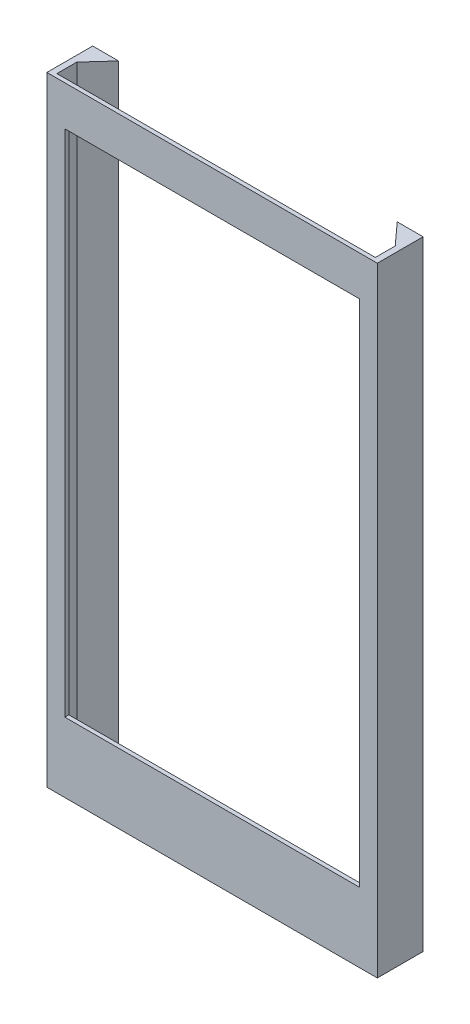
SolidWorks part; units mm, degrees
ref_plane "Alzado" through (0, 0, 0) normal (0, 0, 1) x (1, 0, 0)
ref_plane "Planta" through (0, 0, 0) normal (0, 1, 0) x (1, 0, 0)
ref_plane "Vista lateral" through (0, 0, 0) normal (1, 0, 0) x (0, 0, -1)
sketch "Croquis1" plane through (0, 0, 0) normal (0, 0, 1) x (1, 0, 0)
  line L0 (-40, 77) -> (-41.5, 77)
  line L1 (-40, -77) -> (40, -77) construction
  line L2 (-40, -77) -> (-40, 77) construction
  line L3 (-40, 77) -> (40, 77)
  line L4 (40, -77) -> (40, 77) construction
  line L5 (-40, -77) -> (40, 77) construction
  line L6 (-40, 77) -> (40, -77) construction
  line L7 (-37, 67) -> (37, 67)
  line L8 (-37, 67) -> (-37, -61)
  line L9 (-37, -61) -> (37, -61)
  line L10 (37, 67) -> (37, -61)
  line L11 (-37, 67) -> (37, -61) construction
  line L12 (-37, -61) -> (37, 67) construction
  line L13 (-41.5, 77) -> (-41.5, -78.5)
  line L14 (-41.5, -78.5) -> (41.5, -78.5)
  line L15 (41.5, -78.5) -> (41.5, 77)
  line L16 (41.5, 77) -> (40, 77)
  point P0 (0, 0)
  point P10 (0, 3)
  dimension "D1" = 80
  dimension "D2" = 154
  dimension "D3" = 10
  dimension "D4" = 3
  dimension "D5" = 3
  dimension "D6" = 16
  dimension "D7" = 1.5
  dimension "D8" = 1.5
  dimension "D9" = 1.5
extrude "Saliente-Extruir1" add sketch "Croquis1" along normal blind 11.5
sketch "Croquis2" plane through (0, 0, 0) normal (0, 0, -1) x (-1, 0, 0)
  line L1 (-40, 77) -> (40, 77)
  line L2 (-40, 77) -> (-40, -77)
  line L3 (-40, -77) -> (40, -77)
  line L4 (40, 77) -> (40, -77)
  line L5 (-40, 77) -> (40, -77) construction
  line L6 (-40, -77) -> (40, 77) construction
  point P4 (0, 0)
extrude "Cortar-Extruir1" cut sketch "Croquis2" against normal blind 10.5
sketch "Croquis3" plane through (0, -77, 0) normal (0, 1, 0) x (1, 0, 0)
  line L0 (0, 0) -> (0, 50000) construction
  line L1 (-40, -10.5) -> (-40, 0) construction
  line L3 (-40, -5.5) -> (-35, 0)
  line L4 (-35, 0) -> (-40, 0)
  line L5 (-40, 0) -> (-40, -5.5)
  line L6 (-40, -10.5) -> (40, -10.5) construction
  line L7 (40, 0) -> (40, -5.5)
  line L8 (35, 0) -> (40, 0)
  line L9 (40, -5.5) -> (35, 0)
  point P3 (-40, -7.5214)
  dimension "D1" = 5
  dimension "D2" = 5
extrude "Saliente-Extruir3" add sketch "Croquis3" along normal through all
